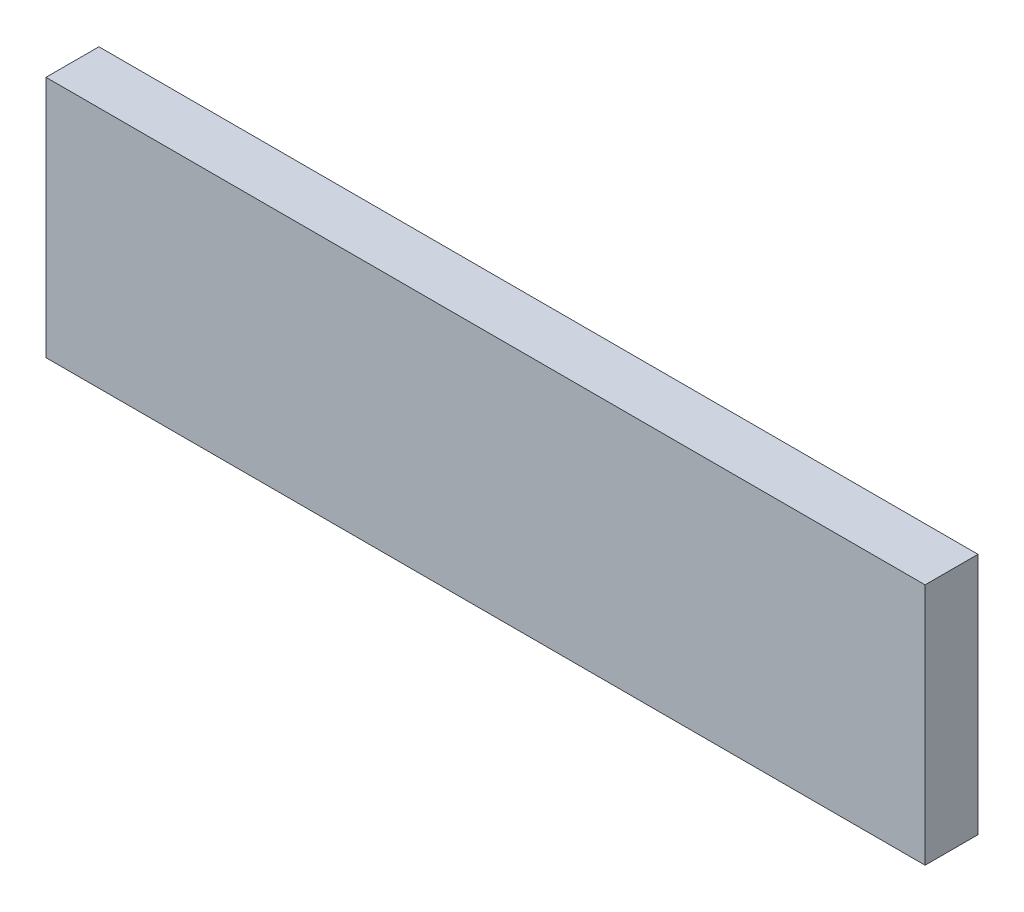
SolidWorks part; units mm, degrees
ref_plane "Front Plane" through (0, 0, 0) normal (0, 0, 1) x (1, 0, 0)
ref_plane "Top Plane" through (0, 0, 0) normal (0, 1, 0) x (1, 0, 0)
ref_plane "Right Plane" through (0, 0, 0) normal (1, 0, 0) x (0, 0, -1)
other "Configuration Table"
sketch "Sketch1" plane through (0, 0, 0) normal (0, 0, 1) x (1, 0, 0)
  line L1 (702, 1469) -> (1350, 1469)
  line L2 (702, 1469) -> (702, 1648)
  line L3 (702, 1648) -> (1350, 1648)
  line L4 (1350, 1469) -> (1350, 1648)
extrude "DET_PU_dilimi_arka_1" add sketch "Sketch1" against normal blind 39 from offset 758.5 separate body
